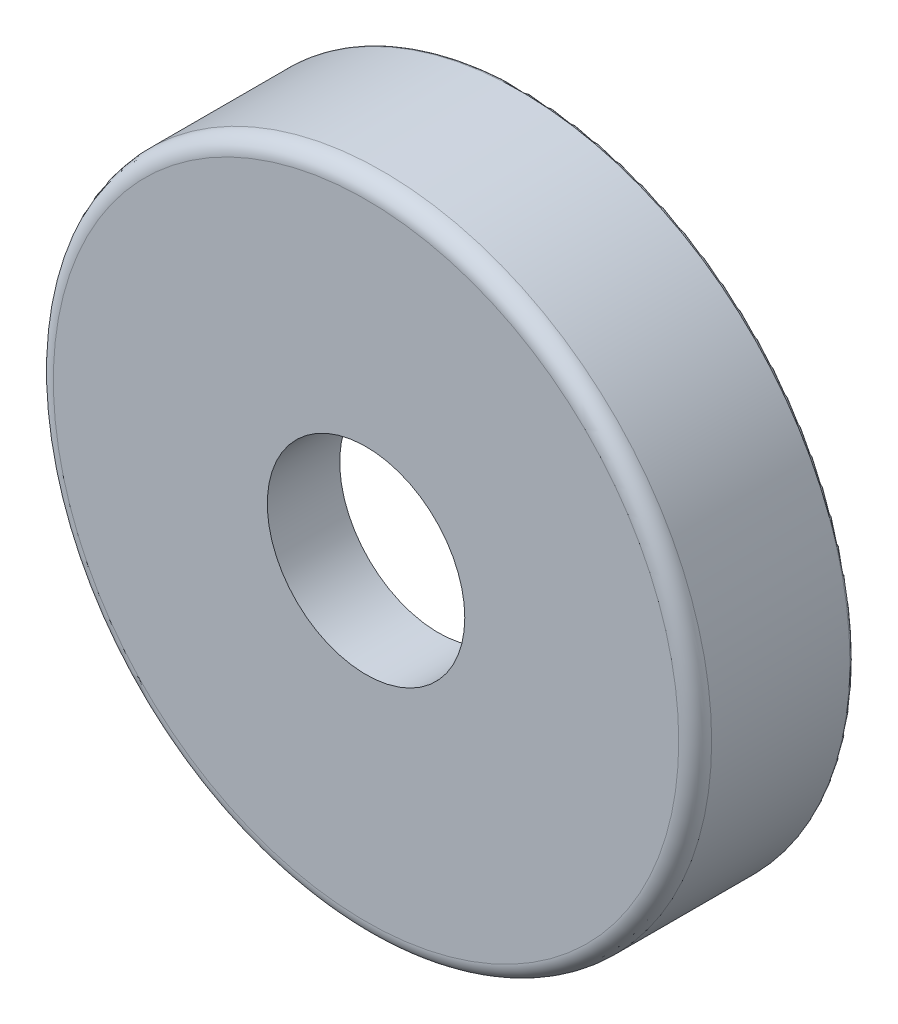
SolidWorks part; units mm, degrees
ref_plane "Front Plane" through (0, 0, 0) normal (0, 0, 1) x (1, 0, 0)
ref_plane "Top Plane" through (0, 0, 0) normal (0, 1, 0) x (1, 0, 0)
ref_plane "Right Plane" through (0, 0, 0) normal (1, 0, 0) x (0, 0, -1)
sketch "Sketch1" plane through (0, 0, 0) normal (0, 0, 1) x (1, 0, 0)
  circle A0 centre (0, 0) radius 10
  circle A1 centre (0, 0) radius 3
  dimension "D1" = 6
  dimension "D2" = 20
extrude "Boss-Extrude1" add sketch "Sketch1" along normal blind 4.8
sketch "Sketch2" plane through (0, 0, 0) normal (0, 1, 0) x (1, 0, 0)
  line L1 (-8.5, -1) -> (-8.5, -1.8)
  line L2 (0, 0) -> (0, 5.619) construction
  line L8 (-8.5, 0) -> (-9.5, 0)
  line L9 (-7.5, -2.8) -> (-4, -2.8)
  line L10 (-4, -2.8) -> (-4, -2.6)
  line L11 (-4, -2.6) -> (-3, -2.6)
  line L12 (-3, -2.6) -> (-3, 0)
  line L13 (-3, 0) -> (-8.5, 0)
  arc A0 (-8.5, -1) -> (-9.5, 0) centre (-9.5, -1) ccw
  arc A1 (-7.5, -2.8) -> (-8.5, -1.8) centre (-7.5, -1.8) cw
  dimension "D5" = 1
  dimension "D6" = 1
  dimension "D1" = 1
  dimension "D2" = 0.2
  dimension "D3" = 2.6
  dimension "D4" = 5.5
revolve "Cut-Revolve1" cut sketch "Sketch2" angle 360 about L2
fillet "Fillet1" radius 0.5 1 edges at (10, 0, 4.8)
fillet "Fillet2" radius 0.1 1 edges at (10, 0, 0)
